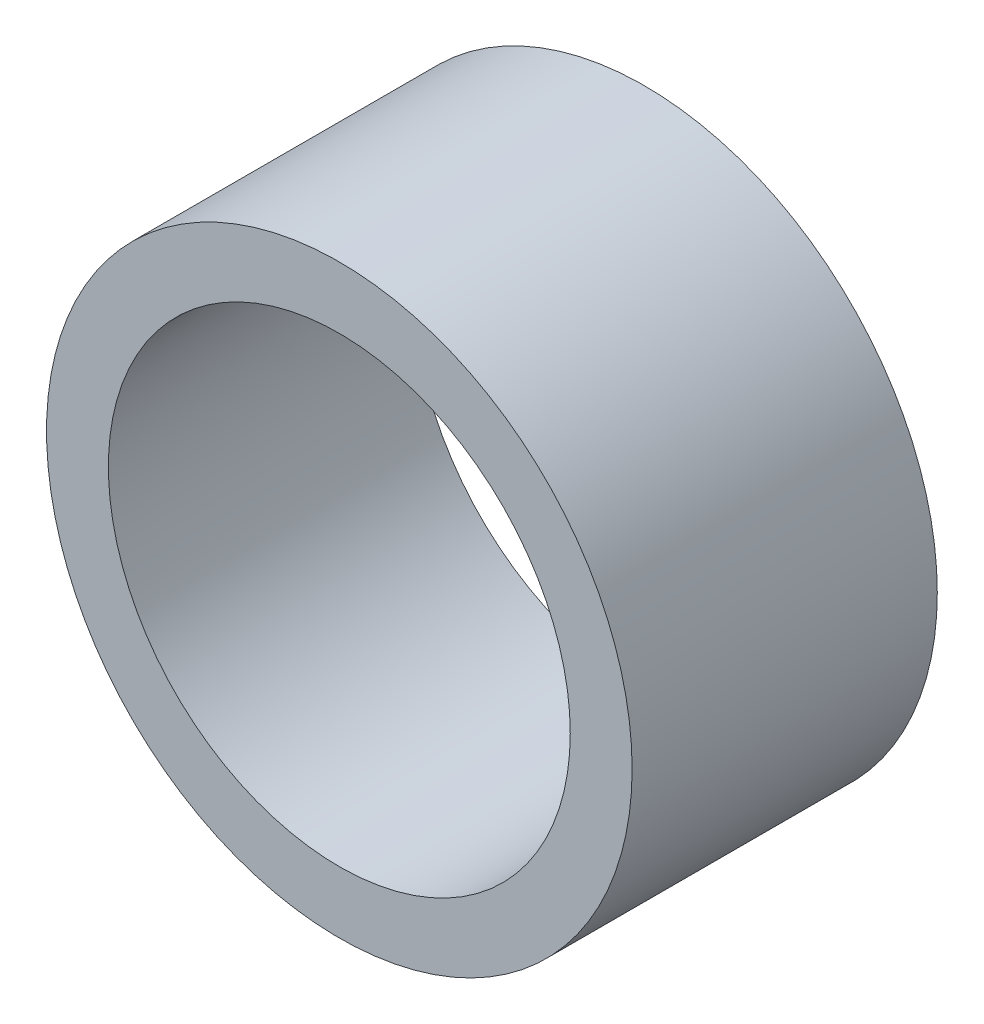
SolidWorks part; units mm, degrees
ref_plane "Plan de face" through (0, 0, 0) normal (0, 0, 1) x (1, 0, 0)
ref_plane "Plan de dessus" through (0, 0, 0) normal (0, 1, 0) x (1, 0, 0)
ref_plane "Plan de droite" through (0, 0, 0) normal (1, 0, 0) x (0, 0, -1)
sketch "Esquisse1" plane through (0, 0, 0) normal (0, 0, 1) x (1, 0, 0)
  circle A0 centre (0, 0) radius 17.75
  circle A1 centre (0, 0) radius 14
  dimension "D1" = 35.5
  dimension "D2" = 28
extrude "Extrusion1" add sketch "Esquisse1" along normal blind 18.5
